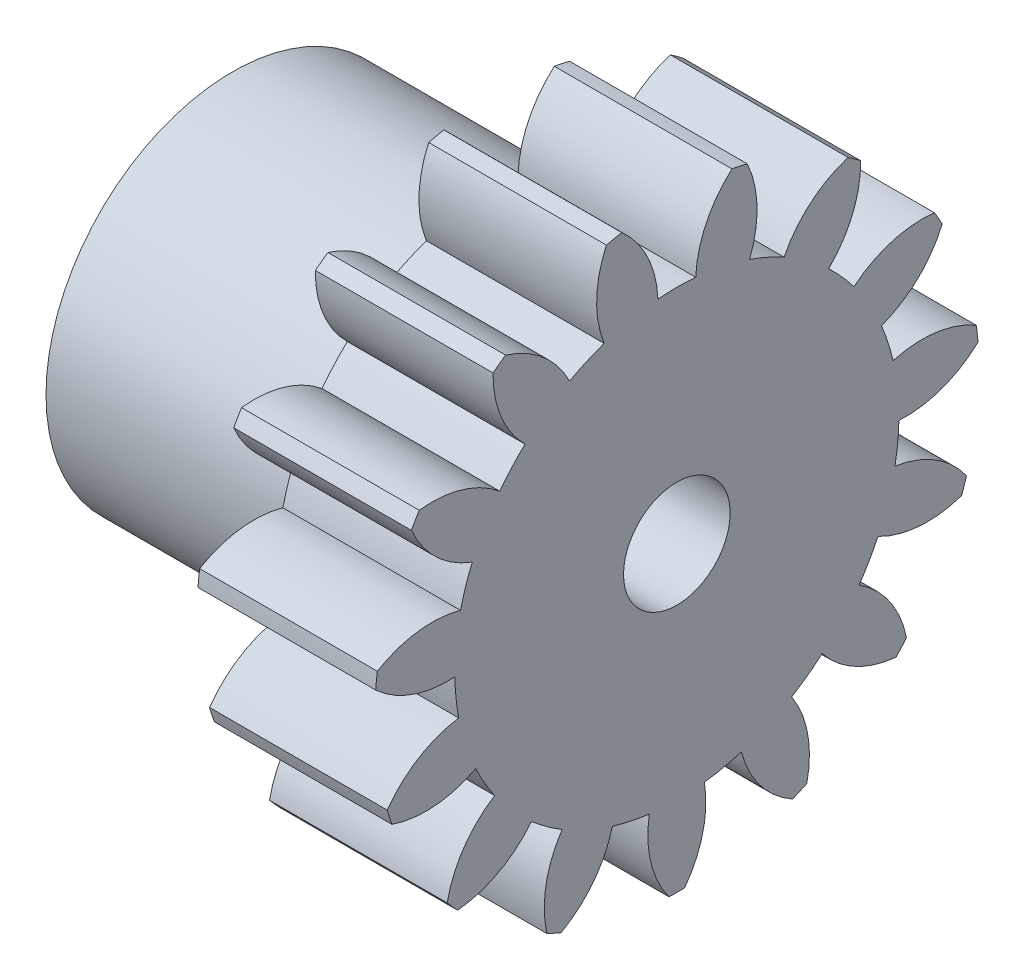
SolidWorks part; units mm, degrees
ref_plane "Plane1" through (0, 0, 0) normal (0, 0, 1) x (1, 0, 0)
ref_plane "Plane2" through (0, 0, 0) normal (0, 1, 0) x (1, 0, 0)
ref_plane "Plane3" through (0, 0, 0) normal (1, 0, 0) x (0, 0, -1)
sketch "HoldingSke" plane through (0, 0, 0) normal (0, 1, 0) x (1, 0, 0)
  line L0 (0, 0) -> (0.9659, -0.2588)
  line L1 (-15, 0) -> (100, 0) construction
  line L2 (0, 0) -> (-2.1039, 2.3779)
  line L3 (0, 0) -> (-11.863, 4.5341)
  line L4 (0, 0) -> (8.3417, 2.2352)
  line L5 (0, 0) -> (-46.8476, -17.4728)
  line L6 (0, 0) -> (-4.1448, -2.7965)
  line L7 (-2.1039, 2.3779) -> (8.6586, 51.2059)
  line L8 (-76.2, 54.61) -> (-75.7, 54.61)
  line L9 (-71.009, 38.7566) -> (-53.1078, 45.2721)
  line L10 (-76.2, 71.12) -> (104.1128, 71.12)
  line L11 (0, 0) -> (-5, 0)
  line L12 (-76.2, 101.6) -> (-76.162, 101.6)
  line L13 (24.9733, 27.94) -> (52.9518, 28.4284)
  line L14 (24.9733, 27.94) -> (24.9743, 27.94)
  line L15 (24.9733, 27.94) -> (100.4006, 29.5858)
  line L16 (-63.627, -1) -> (-12.827, -1)
  circle A0 centre (0, 0) radius 1.5
  circle A1 centre (0, 0) radius 6.249
  circle A2 centre (0, 0) radius 37.5
  circle A3 centre (0, 0) radius 1.5
  dimension "MHD" = 12.498
  dimension "Hub_dia" = 75
  dimension "Bore" = 3
  dimension "MBD" = 3
  dimension "Num_teeth" = 15
  dimension "Pitch" = 1
  dimension "Overall_len" = 50
  dimension "Show_teeth" = 15
  dimension "Thickness" = 5
  dimension "OAL" = 50.0001
  dimension "T_dim" = 0.5
  dimension "Ap" = 20
  dimension "H" = 19.05
  dimension "Pitch_radius" = 180.3128
  dimension "Width" = 5
  dimension "Backlash" = 0.038
  dimension "Addendum_fac" = 1
  dimension "Dedendum_fac" = 1.25
  dimension "Clearance_fac" = 0.25
  dimension "Dedendum_add" = 0.001
  dimension "Module" = 1
sketch "BasProSke" plane through (0, 0, 0) normal (0, 1, 0) x (1, 0, 0)
  line L0 (-10, 0) -> (60, 0) construction
  line L1 (0, 0) -> (0, 8.5)
  line L2 (0, 0) -> (5, 0)
  line L3 (5, 0) -> (5, 8.5)
  line L4 (5, 8.5) -> (0, 8.5)
  dimension "Thickness" = 5
  dimension "Diameter" = 17
revolve "Base-Revolve" add sketch "BasProSke" angle 360 about L0
sketch "TooCutSke" plane through (0, 0, 0) normal (1, 0, 0) x (0, 0, -1)
  line L1 (0, 0) -> (0, 107) construction
  line L2 (0, 0) -> (-0.8504, 7.4516) construction
  line L3 (0, 0) -> (-3.1044, 14.6049) construction
  line L4 (-0.8504, 7.4516) -> (-1.5522, 7.3025) construction
  arc A0 (0.5316, 6.2263) -> (-0.5316, 6.2263) centre (0, 0) ccw
  arc A1 (1.5766, 8.3784) -> (-1.5766, 8.3784) centre (0, 0) ccw
  circle A2 centre (0, 0) radius 7.5 construction
  circle A3 centre (0, 0) radius 7.0477 construction
  arc A4 (-0.5316, 6.2263) -> (-1.5766, 8.3784) centre (-3.5289, 6.1005) ccw
  arc A5 (1.5766, 8.3784) -> (0.5316, 6.2263) centre (3.5289, 6.1005) ccw
  dimension "Root_dia" = 12.498
  dimension "Overcut_dia" = 17.0508
  dimension "Pitch_dia" = 15
  dimension "Base_dia" = 14.0954
  dimension "Flank_rad" = 3
  dimension "Half_ang" = 12
  dimension "Half_CT" = 0.7175
extrude "ToothCut" cut sketch "TooCutSke" along normal through all
fillet "Breaks" [suppressed] radius 0.02
fillet "RootFillets" [suppressed] radius 0.251
pattern_circular "TeethCuts" count 15 every 24 about axis through (-10, 0, 0) along (1, 0, 0) of "ToothCut", "RootFillets", "Breaks"
sketch "HubNeaOneSke" plane through (0, 0, 0) normal (-1, 0, 0) x (0, 0, 1)
  circle A0 centre (0, 0) radius 6.249
  dimension "Diameter" = 12.498
extrude "HubNearOne" [suppressed] add sketch "HubNeaOneSke" along normal blind 45.0001
sketch "HubNeaBotSke" plane through (0, 0, 0) normal (-1, 0, 0) x (0, 0, 1)
  circle A0 centre (0, 0) radius 6.249
  dimension "Diameter" = 12.498
extrude "HubNearBoth" [suppressed] add sketch "HubNeaBotSke" along normal blind 22.5
ref_plane "FarPln" through (5, 0, 0) normal (1, 0, 0) x (0, 0, -1)
sketch "HubFarSke" plane through (5, 0, 0) normal (1, 0, 0) x (0, 0, -1)
  circle A0 centre (0, 0) radius 6.249
  dimension "Diameter" = 12.498
extrude "HubFar" [suppressed] add sketch "HubFarSke" along normal blind 22.5
sketch "BorSke" plane through (0, 0, 0) normal (1, 0, 0) x (0, 0, -1)
  circle A0 centre (0, 0) radius 1.5
  dimension "Diameter" = 3
extrude "Bore" cut sketch "BorSke" along normal mid plane 100.0001
sketch "KeySke" plane through (0, 0, 0) normal (1, 0, 0) x (0, 0, -1)
  line L0 (-0.6, 0) -> (-0.6, 2)
  line L1 (-0.6, 2) -> (0.6, 2)
  line L2 (0.6, 2) -> (0.6, 0)
  line L3 (0, 0) -> (0, 34) construction
  line L4 (-0.6, 0) -> (0.6, 0)
  dimension "Offset" = 2
  dimension "Width" = 1.2
extrude "Keyway" [suppressed] cut sketch "KeySke" along normal mid plane 100.0001
pattern_circular "Keyway2" [suppressed] count 2 every 90 about axis through (-10, 0, 0) along (1, 0, 0)
sketch "Sketch1" plane through (0, 0, 0) normal (-1, 0, 0) x (0, 0, 1)
  line L240 (0.4307, -2.7374) -> (0.6055, -2.8632)
  line L241 (0.3029, -2.9108) -> (0.4307, -2.7374)
  line L242 (0.1422, -2.7674) -> (0.3029, -2.9108)
  line L243 (-0.003, -2.9265) -> (0.1422, -2.7674)
  line L244 (-0.1479, -2.7671) -> (-0.003, -2.9265)
  line L245 (-0.3089, -2.9102) -> (-0.1479, -2.7671)
  line L246 (-0.4363, -2.7365) -> (-0.3089, -2.9102)
  line L247 (-0.6114, -2.862) -> (-0.4363, -2.7365)
  line L248 (-0.72, -2.6759) -> (-0.6114, -2.862)
  line L249 (-0.9072, -2.7824) -> (-0.72, -2.6759)
  line L250 (-0.9957, -2.586) -> (-0.9072, -2.7824)
  line L251 (-1.1931, -2.6723) -> (-0.9957, -2.586)
  line L252 (-1.2606, -2.4677) -> (-1.1931, -2.6723)
  line L253 (-1.4659, -2.5329) -> (-1.2606, -2.4677)
  line L254 (-1.5116, -2.3224) -> (-1.4659, -2.5329)
  line L255 (-1.7226, -2.3658) -> (-1.5116, -2.3224)
  line L256 (-1.7461, -2.1517) -> (-1.7226, -2.3658)
  line L257 (-1.9605, -2.1728) -> (-1.7461, -2.1517)
  line L258 (-1.9615, -1.9574) -> (-1.9605, -2.1728)
  line L259 (-2.1769, -1.956) -> (-1.9615, -1.9574)
  line L260 (-2.1553, -1.7417) -> (-2.1769, -1.956)
  line L261 (-2.3694, -1.7177) -> (-2.1553, -1.7417)
  line L262 (-2.3256, -1.5068) -> (-2.3694, -1.7177)
  line L263 (-2.536, -1.4606) -> (-2.3256, -1.5068)
  line L264 (-2.4703, -1.2555) -> (-2.536, -1.4606)
  line L265 (-2.6748, -1.1876) -> (-2.4703, -1.2555)
  line L266 (-2.588, -0.9904) -> (-2.6748, -1.1876)
  line L267 (-2.7842, -0.9015) -> (-2.588, -0.9904)
  line L268 (-2.6774, -0.7144) -> (-2.7842, -0.9015)
  line L269 (-2.8632, -0.6055) -> (-2.6774, -0.7144)
  line L270 (-2.7374, -0.4307) -> (-2.8632, -0.6055)
  line L271 (-2.9108, -0.3029) -> (-2.7374, -0.4307)
  line L272 (-2.7674, -0.1422) -> (-2.9108, -0.3029)
  line L273 (-2.9265, 0.003) -> (-2.7674, -0.1422)
  line L274 (-2.7671, 0.1479) -> (-2.9265, 0.003)
  line L275 (-2.9102, 0.3089) -> (-2.7671, 0.1479)
  line L276 (-2.7365, 0.4363) -> (-2.9102, 0.3089)
  line L277 (-2.862, 0.6114) -> (-2.7365, 0.4363)
  line L278 (-2.6759, 0.72) -> (-2.862, 0.6114)
  line L279 (-2.7824, 0.9072) -> (-2.6759, 0.72)
  line L280 (-2.586, 0.9957) -> (-2.7824, 0.9072)
  line L281 (-2.6723, 1.1931) -> (-2.586, 0.9957)
  line L282 (-2.4677, 1.2606) -> (-2.6723, 1.1931)
  line L283 (-2.5329, 1.4659) -> (-2.4677, 1.2606)
  line L284 (-2.3224, 1.5116) -> (-2.5329, 1.4659)
  line L285 (-2.3658, 1.7226) -> (-2.3224, 1.5116)
  line L286 (-2.1517, 1.7461) -> (-2.3658, 1.7226)
  line L287 (-2.1728, 1.9605) -> (-2.1517, 1.7461)
  line L288 (-1.9574, 1.9615) -> (-2.1728, 1.9605)
  line L289 (-1.956, 2.1769) -> (-1.9574, 1.9615)
  line L290 (-1.7417, 2.1553) -> (-1.956, 2.1769)
  line L291 (-1.7177, 2.3694) -> (-1.7417, 2.1553)
  line L292 (-1.5068, 2.3256) -> (-1.7177, 2.3694)
  line L293 (-1.4606, 2.536) -> (-1.5068, 2.3256)
  line L294 (-1.2555, 2.4703) -> (-1.4606, 2.536)
  line L295 (-1.1876, 2.6748) -> (-1.2555, 2.4703)
  line L296 (-0.9904, 2.588) -> (-1.1876, 2.6748)
  line L297 (-0.9015, 2.7842) -> (-0.9904, 2.588)
  line L298 (-0.7144, 2.6774) -> (-0.9015, 2.7842)
  line L299 (-0.6055, 2.8632) -> (-0.7144, 2.6774)
  line L300 (-0.4307, 2.7374) -> (-0.6055, 2.8632)
  line L301 (-0.3029, 2.9108) -> (-0.4307, 2.7374)
  line L302 (-0.1422, 2.7674) -> (-0.3029, 2.9108)
  line L303 (0.003, 2.9265) -> (-0.1422, 2.7674)
  line L304 (0.1479, 2.7671) -> (0.003, 2.9265)
  line L305 (0.3089, 2.9102) -> (0.1479, 2.7671)
  line L306 (0.4363, 2.7365) -> (0.3089, 2.9102)
  line L307 (0.6114, 2.862) -> (0.4363, 2.7365)
  line L308 (0.72, 2.6759) -> (0.6114, 2.862)
  line L309 (0.9072, 2.7824) -> (0.72, 2.6759)
  line L310 (0.9957, 2.586) -> (0.9072, 2.7824)
  line L311 (1.1931, 2.6723) -> (0.9957, 2.586)
  line L312 (1.2606, 2.4677) -> (1.1931, 2.6723)
  line L313 (1.4659, 2.5329) -> (1.2606, 2.4677)
  line L314 (1.5116, 2.3224) -> (1.4659, 2.5329)
  line L315 (1.7226, 2.3658) -> (1.5116, 2.3224)
  line L316 (1.7461, 2.1517) -> (1.7226, 2.3658)
  line L317 (1.9605, 2.1728) -> (1.7461, 2.1517)
  line L318 (1.9615, 1.9574) -> (1.9605, 2.1728)
  line L319 (2.1769, 1.956) -> (1.9615, 1.9574)
  line L320 (2.1553, 1.7417) -> (2.1769, 1.956)
  line L321 (2.3694, 1.7177) -> (2.1553, 1.7417)
  line L322 (2.3256, 1.5068) -> (2.3694, 1.7177)
  line L323 (2.536, 1.4606) -> (2.3256, 1.5068)
  line L324 (2.4703, 1.2555) -> (2.536, 1.4606)
  line L325 (2.6748, 1.1876) -> (2.4703, 1.2555)
  line L326 (2.588, 0.9904) -> (2.6748, 1.1876)
  line L327 (2.7842, 0.9015) -> (2.588, 0.9904)
  line L328 (2.6774, 0.7144) -> (2.7842, 0.9015)
  line L329 (2.8632, 0.6055) -> (2.6774, 0.7144)
  line L330 (2.7374, 0.4307) -> (2.8632, 0.6055)
  line L331 (2.9108, 0.3029) -> (2.7374, 0.4307)
  line L332 (2.7674, 0.1422) -> (2.9108, 0.3029)
  line L333 (2.9265, -0.003) -> (2.7674, 0.1422)
  line L334 (2.7671, -0.1479) -> (2.9265, -0.003)
  line L335 (2.9102, -0.3089) -> (2.7671, -0.1479)
  line L336 (2.7365, -0.4363) -> (2.9102, -0.3089)
  line L337 (2.862, -0.6114) -> (2.7365, -0.4363)
  line L338 (2.6759, -0.72) -> (2.862, -0.6114)
  line L339 (2.7824, -0.9072) -> (2.6759, -0.72)
  line L340 (2.586, -0.9957) -> (2.7824, -0.9072)
  line L341 (2.6723, -1.1931) -> (2.586, -0.9957)
  line L342 (2.4677, -1.2606) -> (2.6723, -1.1931)
  line L343 (2.5329, -1.4659) -> (2.4677, -1.2606)
  line L344 (2.3224, -1.5116) -> (2.5329, -1.4659)
  line L345 (2.3658, -1.7226) -> (2.3224, -1.5116)
  line L346 (2.1517, -1.7461) -> (2.3658, -1.7226)
  line L347 (2.1728, -1.9605) -> (2.1517, -1.7461)
  line L348 (1.9574, -1.9615) -> (2.1728, -1.9605)
  line L349 (1.956, -2.1769) -> (1.9574, -1.9615)
  line L350 (1.7417, -2.1553) -> (1.956, -2.1769)
  line L351 (1.7177, -2.3694) -> (1.7417, -2.1553)
  line L352 (1.5068, -2.3256) -> (1.7177, -2.3694)
  line L353 (1.4606, -2.536) -> (1.5068, -2.3256)
  line L354 (1.2555, -2.4703) -> (1.4606, -2.536)
  line L355 (1.1876, -2.6748) -> (1.2555, -2.4703)
  line L356 (0.9904, -2.588) -> (1.1876, -2.6748)
  line L357 (0.9015, -2.7842) -> (0.9904, -2.588)
  line L358 (0.7144, -2.6774) -> (0.9015, -2.7842)
  line L359 (0.6055, -2.8632) -> (0.7144, -2.6774)
  circle A0 centre (0, 0) radius 5.25
extrude "Boss-Extrude1" add sketch "Sketch1" along normal blind 7.5
fillet "Fillet1" radius 0.5 1 edges at (0, 0, -5.25)
equation "' \"Module@HoldingSke\" = 6.35"
equation "' \"Num_teeth@HoldingSke\" = 12"
equation "' \"Ap@HoldingSke\" =  20"
equation "' \"Ap@HoldingSke\" = 20"
equation "' \"Width@HoldingSke\" = 0.5 * 25.4"
equation "' \"Hub_dia@HoldingSke\"= 1 * 25.4"
equation "' \"Hub_dia@HoldingSke\" = 1 * 25.4"
equation "' \"Overall_len@HoldingSke\" = 1.0 * 25.4"
equation "' \"Bore@HoldingSke\" = 0.75 * 25.4"
equation "' \"T_dim@HoldingSke\" = 0.1 * 25.4"
equation "' \"Width@KeySke\" = 0.25 * 25.4"
equation "' \"Show_teeth@HoldingSke\" = 13"
equation "' \"Backlash@HoldingSke\" = 0.009 * 25.4"
equation "' \"Addendum_fac@HoldingSke\" = 1.0"
equation "' \"Dedendum_fac@HoldingSke\" = 1.25"
equation "' \"Dedendum_add@HoldingSke\" = 0.00005 * 25.4"
equation "' \"Clearance_fac@HoldingSke\" = 0.25"
equation "\"Pitch@HoldingSke\" = 1 / \"Module@HoldingSke\""
equation "\"Overcut_dia@TooCutSke\" = (\"Num_teeth@HoldingSke\" + 2 * \"Addendum_fac@HoldingSke\") / \"Pitch@HoldingSke\" + 0.002 * 25.4"
equation "\"Pitch_dia@TooCutSke\" = \"Num_teeth@HoldingSke\" / \"Pitch@HoldingSke\""
equation "\"Base_dia@TooCutSke\" = \"Num_teeth@HoldingSke\" / \"Pitch@HoldingSke\" * cos((\"Ap@HoldingSke\"  * 3.14159265 / 180))"
equation "\"Root_dia@TooCutSke\" = (\"Num_teeth@HoldingSke\" + 2) / \"Pitch@HoldingSke\" - 2 * (\"Addendum_fac@HoldingSke\" + \"Dedendum_fac@HoldingSke\") / \"Pitch@HoldingSke\" - \"Dedendum_add@HoldingSke\" * 2"
equation "\"Half_ang@TooCutSke\" = 180 / \"Num_teeth@HoldingSke\""
equation "\"Half_CT@TooCutSke\" = \"Num_teeth@HoldingSke\" / \"Pitch@HoldingSke\" * sin((3.14159265 / 2 / \"Num_teeth@HoldingSke\")) / 2 - 7 * \"Backlash@HoldingSke\" / 4"
equation "\"Flank_rad@TooCutSke\" = \"Num_teeth@HoldingSke\" / \"Pitch@HoldingSke\" / 5"
equation "\"Radius@RootFillets\" = \"Clearance_fac@HoldingSke\" / \"Pitch@HoldingSke\" + \"Dedendum_add@HoldingSke\""
equation "\"Break_rad@Breaks\" = 0.02 / \"Pitch@HoldingSke\""
equation "\"Thickness@HoldingSke\" = \"Width@HoldingSke\""
equation "\"OAL@HoldingSke\" = \"Thickness@HoldingSke\""
equation "\"MHD@HoldingSke\" = (\"Num_teeth@HoldingSke\" + 2) / \"Pitch@HoldingSke\" - 2 * (\"Addendum_fac@HoldingSke\" + \"Dedendum_fac@HoldingSke\")  / \"Pitch@HoldingSke\" - \"Dedendum_add@HoldingSke\" * 2"
equation "\"MBD@HoldingSke\" = (\"Num_teeth@HoldingSke\" + 2) / \"Pitch@HoldingSke\" - 2 * (\"Addendum_fac@HoldingSke\" + \"Dedendum_fac@HoldingSke\")  / \"Pitch@HoldingSke\" - \"Dedendum_add@HoldingSke\" * 2 - 0.002 * 25.4"
equation "\"MHD@HoldingSke\" = ((sgn( \"MHD@HoldingSke\" - \"Hub_dia@HoldingSke\" )-1)*( \"MHD@HoldingSke\" - \"Hub_dia@HoldingSke\" ))/-2+ \"Hub_dia@HoldingSke\""
equation "\"MBD@HoldingSke\" = ((sgn( \"MBD@HoldingSke\" - \"Bore@HoldingSke\" )-1)*( \"MBD@HoldingSke\" - \"Bore@HoldingSke\" ))/-2+ \"Bore@HoldingSke\""
equation "\"OAL@HoldingSke\" = ((sgn( \"OAL@HoldingSke\" - \"Overall_len@HoldingSke\" )+1)*( \"OAL@HoldingSke\" - \"Overall_len@HoldingSke\" ))/2 + \"Overall_len@HoldingSke\" + 0.000002 * 25.4"
equation "\"Num_teeth@TeethCuts\" = int( \"Show_teeth@HoldingSke\" ) + 1"
equation "\"Num_teeth@TeethCuts\" = ((sgn( \"Num_teeth@TeethCuts\" - \"Num_teeth@HoldingSke\" )-1)*( \"Num_teeth@TeethCuts\" - \"Num_teeth@HoldingSke\" ))/-2+ \"Num_teeth@HoldingSke\""
equation "\"Num_teeth@TeethCuts\" = ((sgn( \"Num_teeth@TeethCuts\" - 2.0)+1)*( \"Num_teeth@TeethCuts\" - 2.0))/2 +2.0"
equation "\"Angle@TeethCuts\" = 360.0 / \"Num_teeth@HoldingSke\""
equation "\"Diameter@BasProSke\" = (\"Num_teeth@HoldingSke\" + 2 * \"Addendum_fac@HoldingSke\") / \"Pitch@HoldingSke\""
equation "\"Thickness@BasProSke\"  = \"Thickness@HoldingSke\""
equation "' \"Fillet_rad@BasProSke\" =  \"Thickness@HoldingSke\" * 0.05"
equation "' \"Fillet_rad@BasProSke\" = \"Thickness@HoldingSke\" * 0.05"
equation "\"MHD@HoldingSke\" = ((sgn( \"MHD@HoldingSke\" - \"Root_dia@TooCutSke\" )-1)*( \"MHD@HoldingSke\" - \"Root_dia@TooCutSke\" ))/-2+ \"Root_dia@TooCutSke\""
equation "\"Diameter@HubNeaOneSke\" = \"MHD@HoldingSke\""
equation "\"Length@HubNearOne\" = \"OAL@HoldingSke\" - \"Thickness@BasProSke\""
equation "\"Diameter@HubNeaBotSke\" = \"MHD@HoldingSke\""
equation "\"Length@HubNearBoth\" = ( \"OAL@HoldingSke\" - \"Thickness@BasProSke\" ) / 2.0"
equation "\"Thickness@FarPln\" = \"Thickness@BasProSke\""
equation "\"Diameter@HubFarSke\" = \"MHD@HoldingSke\""
equation "\"Length@HubFar\" = ( \"OAL@HoldingSke\" - \"Thickness@BasProSke\" ) / 2.0"
equation "\"Diameter@BorSke\" = \"MBD@HoldingSke\""
equation "\"D1@Bore\" = \"OAL@HoldingSke\" * 2.0"
equation "\"D1@Keyway\" = \"OAL@HoldingSke\" * 2.0"
equation "\"Offset@KeySke\" = \"T_dim@HoldingSke\" + \"MBD@HoldingSke\" / 2.0"
